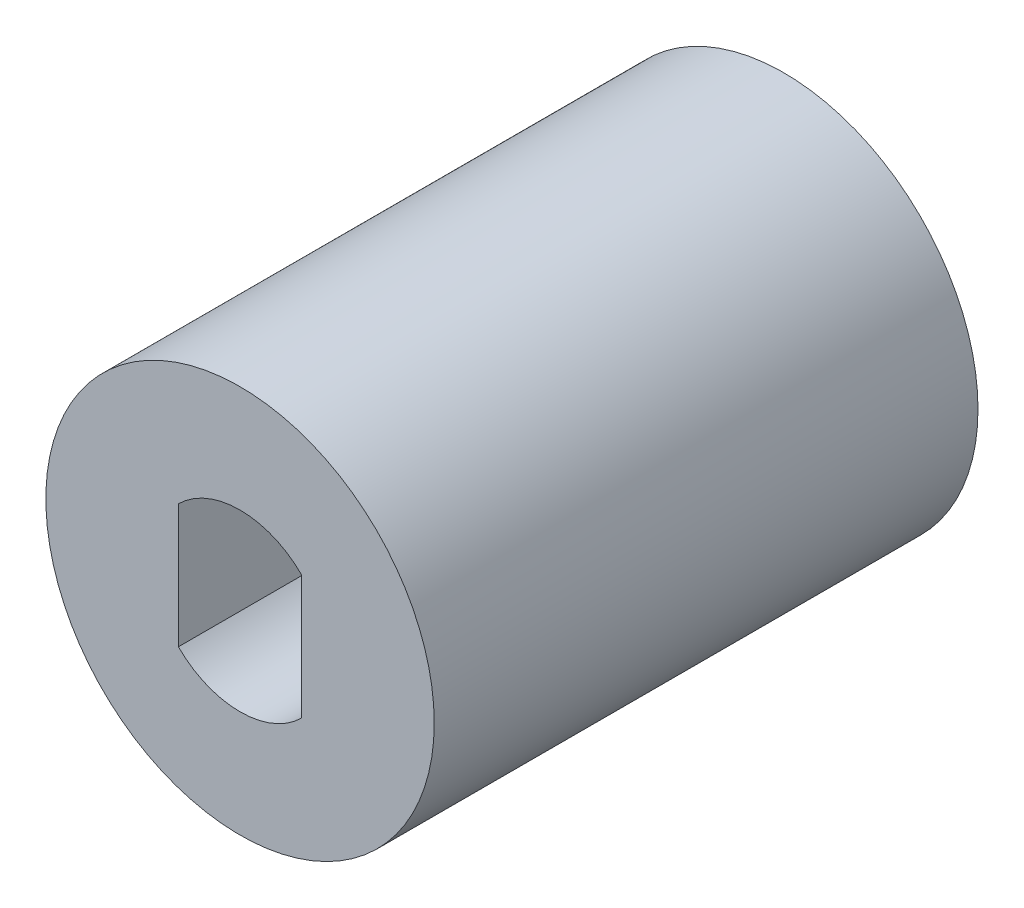
SolidWorks part; units mm, degrees
ref_plane "前视基准面" through (0, 0, 0) normal (0, 0, 1) x (1, 0, 0)
ref_plane "上视基准面" through (0, 0, 0) normal (0, 1, 0) x (1, 0, 0)
ref_plane "右视基准面" through (0, 0, 0) normal (1, 0, 0) x (0, 0, -1)
sketch "草图1" plane through (0, 0, 0) normal (0, 0, 1) x (1, 0, 0)
  line L0 (4, 3) -> (4, -3)
  arc A0 (4, 3) -> (4, -3) centre (0, 0) ccw
  circle A1 centre (0, 0) radius 10
  dimension "D1" = 10
  dimension "D3" = 20
  dimension "D2" = 9
extrude "凸台-拉伸1" add sketch "草图1" along normal mid plane 28
sketch "草图3" plane through (0, 0, 0) normal (0, 0, 1) x (1, 0, 0)
  circle A0 centre (0, 0) radius 6
  dimension "D1" = 12
extrude "切除-拉伸1" cut sketch "草图3" against normal mid plane 10
sketch "草图2" plane through (0, 0, 14) normal (0, 0, 1) x (1, 0, 0)
  line L0 (4, -3) -> (4, 3) construction
  line L1 (4, -3) -> (4, 3)
  line L3 (-3.175, 3.1889) -> (3.175, 3.1889)
  line L4 (-3.175, 3.1889) -> (-3.175, -3.1889)
  line L5 (-3.175, -3.1889) -> (3.175, -3.1889)
  line L6 (3.175, 3.1889) -> (3.175, -3.1889)
  arc A0 (4, 3) -> (4, -3) centre (0, 0) ccw construction
  arc A1 (4, 3) -> (4, -3) centre (0, 0) ccw
  circle A2 centre (0, 0) radius 4.5
  line M3 (4, 3) -> (4, -3)
  arc M4 (4, -3) -> (4, 3) centre (0, 0) cw
  dimension "D1" = 9
  dimension "D2" = 6.35
extrude "凸台-拉伸2" add sketch "草图2" against normal up to surface (9 mm away) contours A2 M3 M4 | L4 A2 | L1 A2 | L1 A2 L6 up to face at (-0.5, 0, 5)
